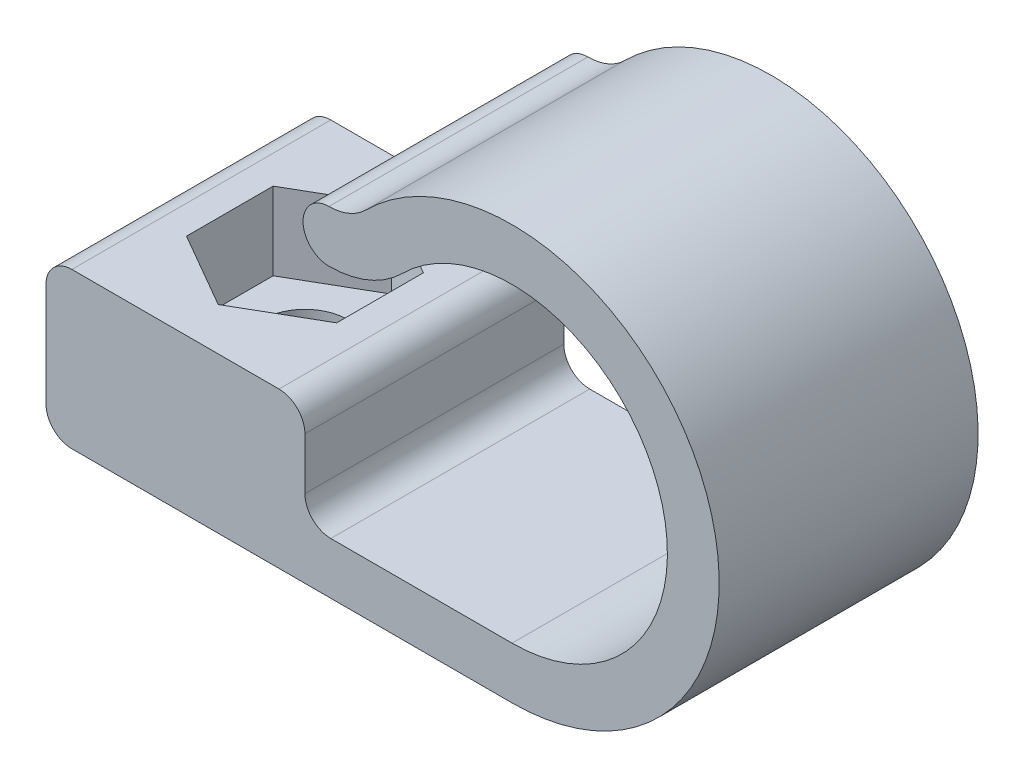
SolidWorks part; units mm, degrees
ref_plane "Front Plane" through (0, 0, 0) normal (0, 0, 1) x (1, 0, 0)
ref_plane "Top Plane" through (0, 0, 0) normal (0, 1, 0) x (1, 0, 0)
ref_plane "Right Plane" through (0, 0, 0) normal (1, 0, 0) x (0, 0, -1)
sketch "Sketch1" plane through (0, 0, 0) normal (0, 0, 1) x (1, 0, 0)
  line L0 (0, 1) -> (0, 5)
  line L1 (1, 6) -> (9, 6)
  line L2 (18, 2) -> (11, 2)
  line L3 (10, 3) -> (10, 5)
  line L4 (1, 0) -> (18, 0)
  arc A1 (18, 2) -> (13.7574, 12.2426) centre (18, 8) ccw
  arc A3 (18, 0) -> (12.3431, 13.6569) centre (18, 8) ccw
  arc A4 (10.9289, 13.0711) -> (12.3431, 13.6569) centre (10.9289, 15.0711) ccw
  arc A5 (10.9289, 11.0711) -> (13.7574, 12.2426) centre (10.9289, 15.0711) ccw
  arc A6 (10.9289, 13.0711) -> (10.9289, 11.0711) centre (10.9289, 12.0711) ccw
  arc A7 (0, 1) -> (1, 0) centre (1, 1) ccw
  arc A8 (0, 5) -> (1, 6) centre (1, 5) cw
  arc A9 (11, 2) -> (10, 3) centre (11, 3) cw
  arc A10 (9, 6) -> (10, 5) centre (9, 5) cw
  point P24 (0, 0)
extrude "Boss-Extrude1" add sketch "Sketch1" along normal blind 10
sketch "Sketch2" plane through (0, 6, 0) normal (0, 1, 0) x (1, 0, 0)
  line L2 (5, -1.6514) -> (2.1, -3.3257)
  line L3 (2.1, -3.3257) -> (2.1, -6.6743)
  line L4 (2.1, -6.6743) -> (5, -8.3486)
  line L5 (5, -8.3486) -> (7.9, -6.6743)
  line L6 (7.9, -6.6743) -> (7.9, -3.3257)
  line L7 (7.9, -3.3257) -> (5, -1.6514)
  circle A0 centre (5, -5) radius 2.9 construction
extrude "Cut-Extrude1" cut sketch "Sketch2" against normal offset from surface (3 mm away) 3 up to face at (9.5, 0, 5)
sketch "Sketch3" plane through (0, 6, 0) normal (0, 1, 0) x (1, 0, 0)
  circle A0 centre (5, -5) radius 1.65
extrude "Cut-Extrude2" cut sketch "Sketch3" against normal up to surface (6 mm away) up to face at (9.5, 0, 5)
